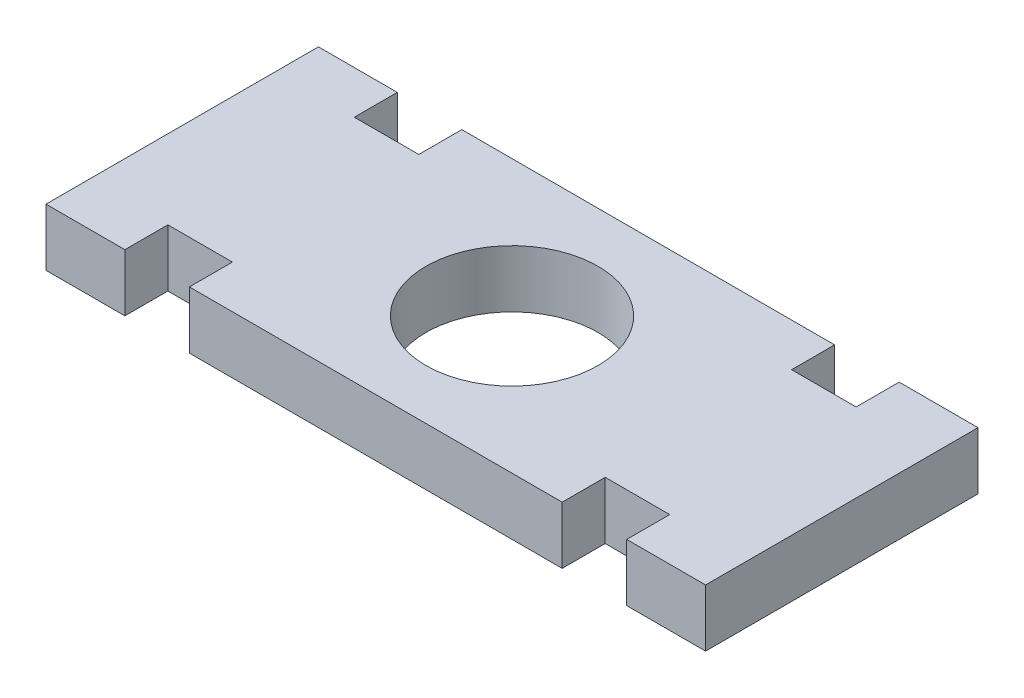
SolidWorks part; units mm, degrees
ref_plane "正面" through (0, 0, 0) normal (0, 0, 1) x (1, 0, 0)
ref_plane "平面" through (0, 0, 0) normal (0, 1, 0) x (1, 0, 0)
ref_plane "右側面" through (0, 0, 0) normal (1, 0, 0) x (0, 0, -1)
sketch "ｽｹｯﾁ1" plane through (0, 0, 0) normal (0, 1, 0) x (1, 0, 0)
  line L0 (-23, 0) -> (-23, 19) construction
  line L1 (0, 0) -> (-5.5, 0)
  line L2 (0, 0) -> (0, 19)
  line L3 (0, 19) -> (-5.5, 19)
  line L4 (-46, 0) -> (-46, 19)
  line L5 (0, 9.5) -> (-46, 9.5) construction
  line L6 (-36, 0) -> (-36, 3)
  line L7 (-10, 19) -> (-36, 19)
  line L8 (-40.5, 19) -> (-40.5, 16)
  line L9 (-40.5, 16) -> (-36, 16)
  line L10 (-36, 19) -> (-36, 16)
  line L11 (-40.5, 3) -> (-36, 3)
  line L12 (-40.5, 0) -> (-40.5, 3)
  line L13 (-10, 0) -> (-10, 3)
  line L14 (-5.5, 0) -> (-5.5, 3)
  line L15 (-5.5, 3) -> (-10, 3)
  line L16 (-5.5, 19) -> (-5.5, 16)
  line L17 (-5.5, 16) -> (-10, 16)
  line L18 (-10, 19) -> (-10, 16)
  line L19 (-40.5, 19) -> (-46, 19)
  line L20 (-10, 0) -> (-36, 0)
  line L21 (-40.5, 0) -> (-46, 0)
  circle A0 centre (-23, 9.5) radius 6
  dimension "D6" = 12
  dimension "D1" = 46
  dimension "D2" = 19
  dimension "D3" = 5.5
  dimension "D4" = 3
  dimension "D5" = 4.5
extrude "ﾎﾞｽ - 押し出し1" add sketch "ｽｹｯﾁ1" along normal blind 4
